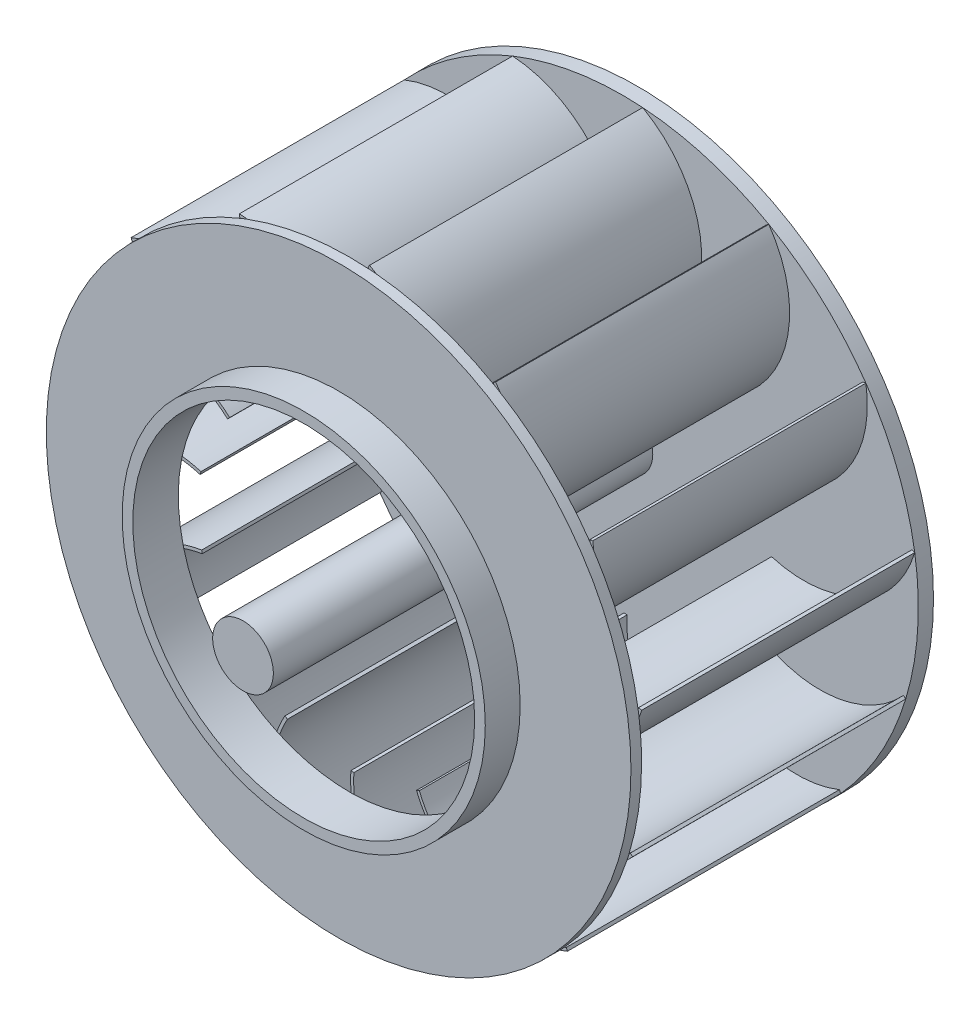
SolidWorks part; units mm, degrees
ref_plane "Front Plane" through (0, 0, 0) normal (0, 0, 1) x (1, 0, 0)
ref_plane "Top Plane" through (0, 0, 0) normal (0, 1, 0) x (1, 0, 0)
ref_plane "Right Plane" through (0, 0, 0) normal (1, 0, 0) x (0, 0, -1)
sketch "Sketch1" plane through (0, 0, 0) normal (0, 0, 1) x (1, 0, 0)
  circle A0 centre (0, 0) radius 19.5
  dimension "D1" = 39
extrude "Boss-Extrude1" add sketch "Sketch1" along normal mid plane 1
sketch "Sketch2" plane through (0, 0, 0.5) normal (0, 0, 1) x (1, 0, 0)
  line L0 (0, 0) -> (1.3378, 19.4541) construction
  line L1 (0, 0) -> (8.2751, 17.6571) construction
  line L2 (0, 0) -> (14.0948, 13.4754) construction
  line L3 (0, 0) -> (18.0109, 7.4739) construction
  line L4 (0, 0) -> (19.4945, 0.4629) construction
  line L5 (0, 0) -> (18.3453, -6.6106) construction
  line L6 (0, 0) -> (14.7185, -12.7913) construction
  line L7 (0, 0) -> (9.1038, -17.2444) construction
  line L8 (0, 0) -> (2.2596, -19.3686) construction
  line L9 (0, 0) -> (-4.8897, -18.877) construction
  line L10 (0, 0) -> (-11.3787, -15.8359) construction
  line L11 (0, 0) -> (-16.3309, -10.6561) construction
  line L12 (0, 0) -> (-19.0775, -4.0371) construction
  line L13 (0, 0) -> (-19.2476, 3.1271) construction
  line L14 (0, 0) -> (-16.8182, 9.869) construction
  line L15 (0, 0) -> (-12.1175, 15.278) construction
  line L16 (0, 0) -> (-5.7801, 18.6236) construction
  line L17 (1.3378, 19.4541) -> (1.2397, 19.2798)
  line L18 (4.0694, 9.1531) -> (4.2436, 9.0549)
  circle A0 centre (0, 0) radius 19.5 construction
  circle A1 centre (0, 0) radius 10 construction
  circle A2 centre (0, 0) radius 10 construction
  circle A3 centre (0, 0) radius 10 construction
  circle A4 centre (0, 0) radius 10 construction
  circle A5 centre (0, 0) radius 10 construction
  circle A6 centre (0, 0) radius 10 construction
  circle A7 centre (0, 0) radius 10 construction
  circle A8 centre (0, 0) radius 10 construction
  circle A9 centre (0, 0) radius 10 construction
  circle A10 centre (0, 0) radius 10 construction
  circle A11 centre (0, 0) radius 10 construction
  circle A12 centre (0, 0) radius 10 construction
  circle A13 centre (0, 0) radius 10 construction
  circle A14 centre (0, 0) radius 10 construction
  circle A15 centre (0, 0) radius 10 construction
  circle A16 centre (0, 0) radius 10 construction
  circle A17 centre (0, 0) radius 10 construction
  arc A18 (1.3378, 19.4541) -> (4.2436, 9.0549) centre (-2.4088, 12.8016) cw
  arc A19 (1.2397, 19.2798) -> (4.0694, 9.1531) centre (-2.4088, 12.8016) cw
  point P40 (0, 0)
  dimension "D1" = 20
  dimension "D3" = 0.2
  dimension "D2" = 17
extrude "Boss-Extrude2" add sketch "Sketch2" along normal blind 18
pattern_circular "CirPattern1" count 18 over 360 about axis through (0, 0, 0.5) along (0, 0, 1) of "Boss-Extrude1"
pattern_circular "CirPattern2" count 14 over 360 about axis through (0, 0, 0.5) along (0, 0, 1) of "CirPattern1"
pattern_circular "CirPattern3" count 14 over 360 about axis through (0, 0, 0) along (0, 0, 1) of "Boss-Extrude2"
sketch "Sketch3" plane through (0, 0, 0) normal (0, 1, 0) x (1, 0, 0)
  line L0 (-19.264, -18.5) -> (-16.564, -18.5)
  line L1 (-18.6686, -18.5) -> (-7.8836, -18.5) construction
  line L2 (-16.564, -18.5) -> (-16.564, -4.5087)
  line L3 (-16.564, -4.5087) -> (-16.264, -4.5087)
  line L4 (-16.264, -4.5087) -> (-16.264, -18.8)
  line L5 (-16.264, -18.8) -> (-19.264, -18.8)
  line L6 (-19.264, -18.8) -> (-19.264, -18.5)
  point P9 (0, 0)
  dimension "D1" = 0.3
  dimension "D2" = 0.3
  dimension "D3" = 3
sketch3d "3DSketch1"
  line L0 (0, 0, 0) -> (0, 0, 8.4822) construction
  line L1 (0, 0, 0.5) -> (0, 0, -0.5) construction
sketch "Sketch4" plane through (0, 0, 0.5) normal (0, 0, 1) x (1, 0, 0)
  circle A0 centre (0, 0) radius 2
  dimension "D1" = 4
extrude "Boss-Extrude3" add sketch "Sketch4" along normal blind 25 and the other way blind 13
fillet "Fillet1" radius 0.7 1 edges at (9.8006, -2.0265, 18.5)
sketch "Sketch5" plane through (0, 0, 0) normal (0, 1, 0) x (1, 0, 0)
  line L0 (-19.264, -18.5) -> (-11.264, -18.5)
  line L1 (-14.3757, -18.5) -> (-4.4336, -18.5) construction
  line L2 (-11.264, -18.5) -> (-11.264, -21.5)
  line L3 (-19.264, -19.2) -> (-11.964, -19.2)
  line L4 (-11.964, -19.2) -> (-11.964, -21.5)
  line L5 (-19.264, -18.5) -> (-19.264, -19.2)
  line L6 (-11.964, -21.5) -> (-11.264, -21.5)
  dimension "D2" = 8
  dimension "D3" = 3
  dimension "D1" = 0.7
sketch3d "3DSketch2"
  line L0 (0, 0, 0) -> (0, 0, -45.351) construction
revolve "Revolve2" add sketch "Sketch5" angle 360 about L0
